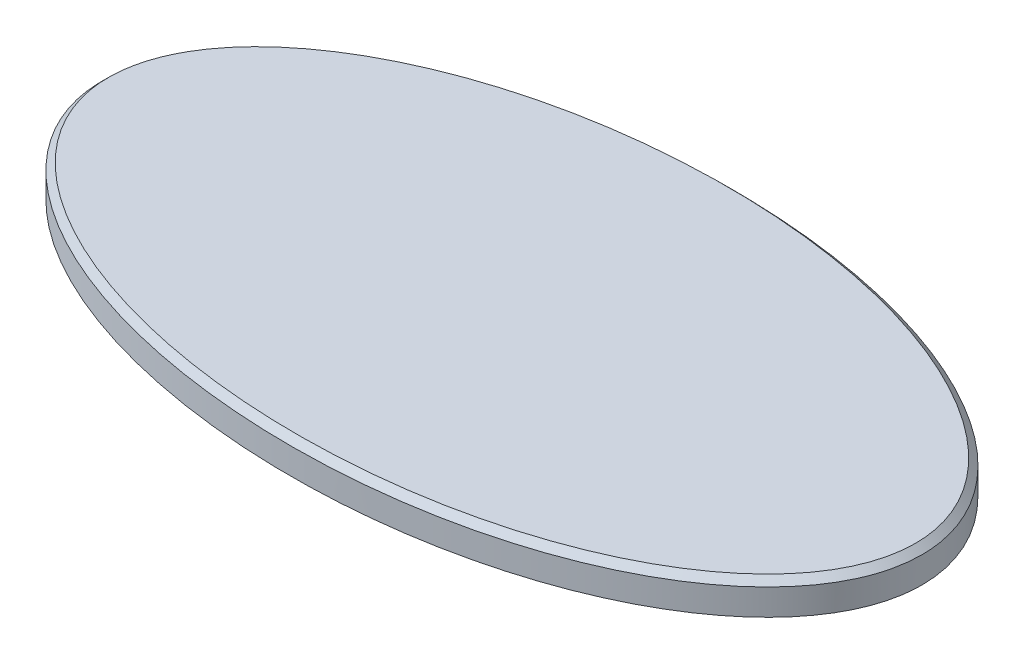
SolidWorks part; units mm, degrees
ref_plane "Front Plane" through (0, 0, 0) normal (0, 0, 1) x (1, 0, 0)
ref_plane "Top Plane" through (0, 0, 0) normal (0, 1, 0) x (1, 0, 0)
ref_plane "Right Plane" through (0, 0, 0) normal (1, 0, 0) x (0, 0, -1)
sketch "Sketch1" plane through (0, 0, 0) normal (0, 1, 0) x (1, 0, 0)
  line L0 (-125, 0) -> (125, 0) construction
  ellipse E0 centre (0, 0) end of major axis (125, 0) minor radius 67.5
  dimension "D1" = 250
  dimension "D2" = 135
extrude "Boss-Extrude1" add sketch "Sketch1" along normal blind 10 contours E0
chamfer "Chamfer1" distance 2 1 edges at (125, 10, 0)
